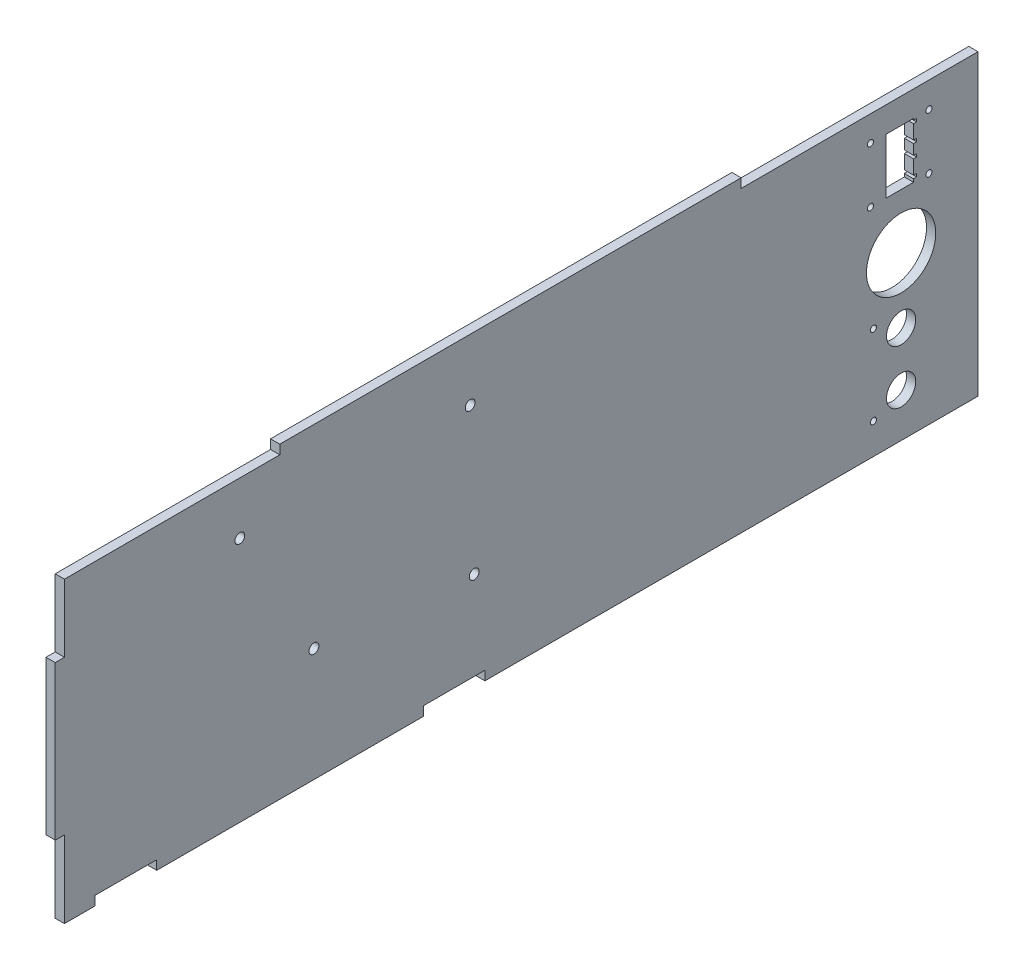
SolidWorks part; units mm, degrees
ref_plane "Plan de face" through (0, 0, 0) normal (0, 0, 1) x (1, 0, 0)
ref_plane "Plan de dessus" through (0, 0, 0) normal (0, 1, 0) x (1, 0, 0)
ref_plane "Plan de droite" through (0, 0, 0) normal (1, 0, 0) x (0, 0, -1)
ref_plane "Plan1" through (3, 0, 0) normal (1, 0, 0) x (0, 0, -1)
sketch "Esquisse1" plane through (3, 0, 0) normal (1, 0, 0) x (0, 0, -1)
  line L0 (77.4232, 44.8541) -> (76.4232, 44.8541)
  line L1 (76.4232, 44.8541) -> (76.4232, 43.8541)
  line L2 (76.4232, 43.8541) -> (67.4232, 43.8541)
  line L3 (67.4232, 43.8541) -> (67.4232, 61.8541)
  line L4 (67.4232, 61.8541) -> (76.4232, 61.8541)
  line L5 (76.4232, 61.8541) -> (76.4232, 61.3541)
  line L6 (76.4232, 61.3541) -> (77.4232, 61.3541)
  line L7 (77.4232, 61.3541) -> (77.4232, 60.3541)
  line L8 (77.4232, 60.3541) -> (76.4232, 60.3541)
  line L9 (76.4232, 60.3541) -> (76.4232, 55.7541)
  line L10 (76.4232, 55.7541) -> (77.4232, 55.7541)
  line L11 (77.4232, 55.7541) -> (77.4232, 54.7541)
  line L12 (77.4232, 54.7541) -> (76.4232, 54.7541)
  line L13 (76.4232, 54.7541) -> (76.4232, 51.4541)
  line L14 (76.4232, 51.4541) -> (77.4232, 51.4541)
  line L15 (77.4232, 51.4541) -> (77.4232, 50.4541)
  line L16 (77.4232, 50.4541) -> (76.4232, 50.4541)
  line L17 (76.4232, 50.4541) -> (76.4232, 45.8541)
  line L18 (76.4232, 45.8541) -> (77.4232, 45.8541)
  line L19 (77.4232, 45.8541) -> (77.4232, 44.8541)
  line L24 (-199.6268, -26.8459) -> (-189.6268, -26.8459)
  line L25 (-189.6268, -26.8459) -> (-189.6268, -23.8459)
  line L26 (-189.6268, -23.8459) -> (-169.6268, -23.8459)
  line L27 (-169.6268, -23.8459) -> (-169.6268, -26.8459)
  line L28 (-169.6268, -26.8459) -> (-82.9268, -26.8459)
  line L29 (-82.9268, -26.8459) -> (-82.9268, -23.8459)
  line L30 (-82.9268, -23.8459) -> (-62.9268, -23.8459)
  line L31 (-62.9268, -23.8459) -> (-62.9268, -26.8459)
  line L32 (-62.9268, -26.8459) -> (97.3732, -26.8459)
  line L33 (97.3732, -26.8459) -> (97.3732, 70.1541)
  line L34 (97.3732, 70.1541) -> (20.3732, 70.1541)
  line L35 (20.3732, 70.1541) -> (20.3732, 73.1541)
  line L36 (20.3732, 73.1541) -> (-129.6268, 73.1541)
  line L37 (-129.6268, 73.1541) -> (-129.6268, 70.1541)
  line L38 (-129.6268, 70.1541) -> (-199.6268, 70.1541)
  line L39 (-199.6268, 70.1541) -> (-199.6268, 48.1541)
  line L40 (-199.6268, 48.1541) -> (-202.6268, 48.1541)
  line L41 (-202.6268, 48.1541) -> (-202.6268, -1.8459)
  line L42 (-202.6268, -1.8459) -> (-199.6268, -1.8459)
  line L43 (-199.6268, -1.8459) -> (-199.6268, -26.8459)
  circle A0 centre (63.3732, -16.8459) radius 1
  circle A1 centre (72.3732, 4.9041) radius 4.75
  circle A2 centre (-67.7268, 53.1541) radius 1.6
  circle A3 centre (-118.5268, 10.0541) radius 1.6
  circle A4 centre (-142.6268, 53.1541) radius 1.6
  circle A5 centre (-66.4268, 4.9541) radius 1.6
  circle A6 centre (72.3732, -12.5959) radius 4.75
  circle A7 centre (63.3732, 9.1541) radius 1
  circle A8 centre (62.4232, 43.8541) radius 1
  circle A9 centre (62.4232, 61.8541) radius 1
  circle A10 centre (72.3732, 25.9966) radius 11.265
  circle A11 centre (81.4232, 43.8541) radius 1
  circle A12 centre (81.4232, 61.8541) radius 1
  point P66 (71.8497, 52.7503)
  dimension "D2" = 22.53
  dimension "D1" = 5
  dimension "D3" = 5
  dimension "D4" = 5
  dimension "D5" = 5
  dimension "D6" = 9
  dimension "D7" = 1
  dimension "D8" = 0.5
  dimension "D9" = 1
  dimension "D10" = 3.3
  dimension "D11" = 1
  dimension "D12" = 4.6
  dimension "D13" = 4.6
  dimension "D14" = 1
  dimension "D15" = 1
extrude "Boss.-Extru.1" add sketch "Esquisse1" against normal blind 3
